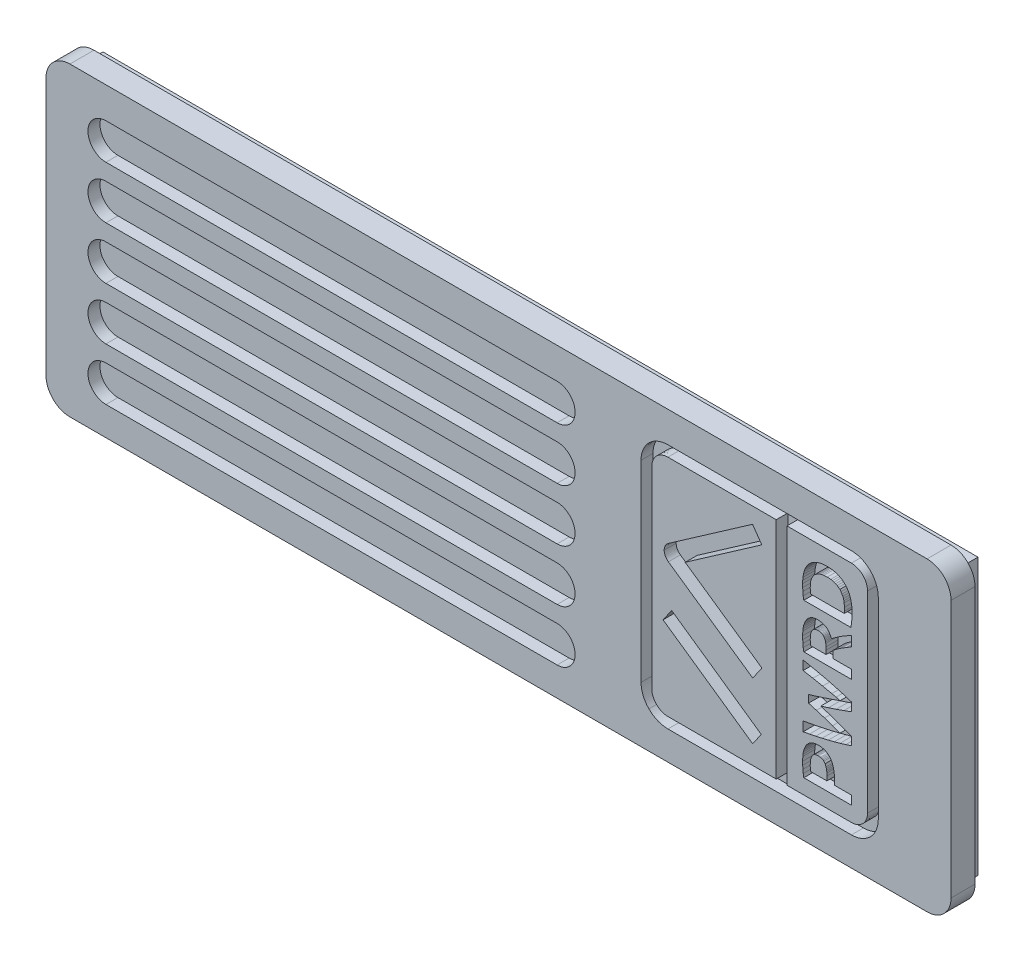
SolidWorks part; units mm, degrees
ref_plane "Front Plane" through (0, 0, 0) normal (0, 0, 1) x (1, 0, 0)
ref_plane "Top Plane" through (0, 0, 0) normal (0, 1, 0) x (1, 0, 0)
ref_plane "Right Plane" through (0, 0, 0) normal (1, 0, 0) x (0, 0, -1)
sketch "Sketch1" plane through (0, 0, 0) normal (0, 0, 1) x (1, 0, 0)
  line L1 (-35.125, 12.5203) -> (40.375, 12.5203)
  line L2 (-35.125, 12.5203) -> (-35.125, -12.9797)
  line L3 (-35.125, -12.9797) -> (40.375, -12.9797)
  line L4 (40.375, 12.5203) -> (40.375, -12.9797)
  dimension "D1" = 25.5
  dimension "D2" = 75.5
extrude "Boss-Extrude1" add sketch "Sketch1" along normal blind 2
sketch "Sketch2" plane through (0, 0, 0) normal (0, 0, -1) x (-1, 0, 0)
  line L0 (-40.375, -12.9797) -> (-40.375, 12.5203) construction
  line L1 (-39.125, 11.2703) -> (33.875, 11.2703)
  line L2 (-39.125, 11.2703) -> (-39.125, -11.7297)
  line L3 (-39.125, -11.7297) -> (33.875, -11.7297)
  line L4 (33.875, 11.2703) -> (33.875, -11.7297)
  line L5 (-40.375, 12.5203) -> (35.125, 12.5203) construction
  line L6 (35.125, -12.9797) -> (-40.375, -12.9797) construction
  line L7 (35.125, 12.5203) -> (35.125, -12.9797) construction
  line L9 (-38.625, 10.7703) -> (33.375, 10.7703)
  line L10 (-38.625, 10.7703) -> (-38.625, -11.2297)
  line L11 (-38.625, -11.2297) -> (33.375, -11.2297)
  line L12 (33.375, 10.7703) -> (33.375, -11.2297)
  dimension "D1" = 1.25
  dimension "D2" = 1.25
  dimension "D3" = 1.25
  dimension "D4" = 1.25
  dimension "D5" = 0.5
  dimension "D6" = 0.5
  dimension "D7" = 0.5
  dimension "D8" = 0.5
extrude "Boss-Extrude2" add sketch "Sketch2" along normal blind 1.5
fillet "Fillet1" radius 2 4 edges at (40.375, 12.5203, 1) (40.375, -12.9797, 1) (-35.125, -12.9797, 1) (-35.125, 12.5203, 1)
sketch "Sketch4" plane through (0, 0, 2) normal (0, 0, 1) x (1, 0, 0)
  line L4 (14.5143, -8.3343) -> (14.5143, 7.713)
  line L5 (16.7569, 9.9556) -> (32.0631, 9.9556)
  line L6 (34.3057, 7.713) -> (34.3057, -8.3343)
  line L7 (32.0631, -10.5769) -> (16.7569, -10.5769)
  line L8 (26.6901, 9.0585) -> (26.6901, -9.6798)
  line L9 (26.6901, -9.6798) -> (32.0631, -9.6798)
  line L10 (33.4087, -8.3343) -> (33.4087, 7.713)
  line L11 (32.0631, 9.0585) -> (26.6901, 9.0585)
  line L12 (28.094, -8.4335) -> (28.0437, -8.1511)
  line L13 (28.0437, -8.1511) -> (28.0159, -7.8656)
  line L14 (28.0159, -7.8656) -> (28.0016, -7.5789)
  line L15 (28.0016, -7.5789) -> (27.996, -7.2918)
  line L16 (27.996, -7.2918) -> (28.0095, -6.9377)
  line L17 (28.0095, -6.9377) -> (28.0265, -6.7634)
  line L18 (28.0265, -6.7634) -> (28.0561, -6.5922)
  line L19 (28.0561, -6.5922) -> (28.1028, -6.4253)
  line L20 (28.1028, -6.4253) -> (28.1647, -6.2624)
  line L21 (28.1647, -6.2624) -> (28.2373, -6.1022)
  line L22 (28.2373, -6.1022) -> (28.3154, -5.9434)
  line L23 (28.3154, -5.9434) -> (28.417, -5.8361)
  line L24 (28.417, -5.8361) -> (28.5218, -5.7352)
  line L25 (28.5218, -5.7352) -> (28.6328, -5.6473)
  line L26 (28.6328, -5.6473) -> (28.692, -5.6102)
  line L27 (28.692, -5.6102) -> (28.7539, -5.5788)
  line L28 (28.7539, -5.5788) -> (28.8185, -5.553)
  line L29 (28.8185, -5.553) -> (28.8858, -5.5324)
  line L30 (28.8858, -5.5324) -> (29.0254, -5.5034)
  line L31 (29.0254, -5.5034) -> (29.1706, -5.486)
  line L32 (29.1706, -5.486) -> (29.3187, -5.4745)
  line L33 (29.3187, -5.4745) -> (29.476, -5.482)
  line L34 (29.476, -5.482) -> (29.6305, -5.502)
  line L35 (29.6305, -5.502) -> (29.7804, -5.5438)
  line L36 (29.7804, -5.5438) -> (29.9274, -5.5997)
  line L37 (29.9274, -5.5997) -> (30.0475, -5.6717)
  line L38 (30.0475, -5.6717) -> (30.1584, -5.7541)
  line L39 (30.1584, -5.7541) -> (30.2542, -5.8538)
  line L40 (30.2542, -5.8538) -> (30.3413, -5.9637)
  line L41 (30.3413, -5.9637) -> (30.4193, -6.1016)
  line L42 (30.4193, -6.1016) -> (30.4866, -6.2438)
  line L43 (30.4866, -6.2438) -> (30.5368, -6.393)
  line L44 (30.5368, -6.393) -> (30.5772, -6.5462)
  line L45 (30.5772, -6.5462) -> (30.6113, -6.7414)
  line L46 (30.6113, -6.7414) -> (30.6364, -6.9373)
  line L47 (30.6364, -6.9373) -> (30.6489, -7.1346)
  line L48 (30.6489, -7.1346) -> (30.6535, -7.3326)
  line L49 (30.6535, -7.3326) -> (30.6535, -7.6996)
  line L50 (30.6535, -7.6996) -> (32.0748, -7.6996)
  line L51 (32.0748, -7.6996) -> (32.0748, -8.4335)
  line L52 (32.0748, -8.4335) -> (28.094, -8.4335)
  line L53 (28.4871, 7.186) -> (28.6281, 7.3283)
  line L54 (28.6281, 7.3283) -> (28.7016, 7.3948)
  line L55 (28.7016, 7.3948) -> (28.7797, 7.4559)
  line L56 (28.7797, 7.4559) -> (28.8622, 7.5104)
  line L57 (28.8622, 7.5104) -> (28.9483, 7.5595)
  line L58 (28.9483, 7.5595) -> (29.1275, 7.6491)
  line L59 (29.1275, 7.6491) -> (29.3524, 7.722)
  line L60 (29.3524, 7.722) -> (29.4659, 7.7527)
  line L61 (29.4659, 7.7527) -> (29.5806, 7.7765)
  line L62 (29.5806, 7.7765) -> (29.6969, 7.7925)
  line L63 (29.6969, 7.7925) -> (29.8142, 7.8025)
  line L64 (29.8142, 7.8025) -> (30.0508, 7.8121)
  line L65 (30.0508, 7.8121) -> (30.2844, 7.8022)
  line L66 (30.2844, 7.8022) -> (30.4003, 7.7921)
  line L67 (30.4003, 7.7921) -> (30.515, 7.7761)
  line L68 (30.515, 7.7761) -> (30.6283, 7.7522)
  line L69 (30.6283, 7.7522) -> (30.7403, 7.7216)
  line L70 (30.7403, 7.7216) -> (30.9623, 7.6491)
  line L71 (30.9623, 7.6491) -> (31.1426, 7.5591)
  line L72 (31.1426, 7.5591) -> (31.2296, 7.5098)
  line L73 (31.2296, 7.5098) -> (31.313, 7.4553)
  line L74 (31.313, 7.4553) -> (31.3919, 7.3943)
  line L75 (31.3919, 7.3943) -> (31.4664, 7.3279)
  line L76 (31.4664, 7.3279) -> (31.6093, 7.186)
  line L77 (31.6093, 7.186) -> (31.7323, 7.0199)
  line L78 (31.7323, 7.0199) -> (31.7888, 6.9343)
  line L79 (31.7888, 6.9343) -> (31.8399, 6.8457)
  line L80 (31.8399, 6.8457) -> (31.8848, 6.7535)
  line L81 (31.8848, 6.7535) -> (31.9242, 6.6585)
  line L82 (31.9242, 6.6585) -> (31.9942, 6.4637)
  line L83 (31.9942, 6.4637) -> (32.0489, 6.2332)
  line L84 (32.0489, 6.2332) -> (32.0902, 6.0009)
  line L85 (32.0902, 6.0009) -> (32.1108, 5.7657)
  line L86 (32.1108, 5.7657) -> (32.1192, 5.5288)
  line L87 (32.1192, 5.5288) -> (32.1132, 5.252)
  line L88 (32.1132, 5.252) -> (32.0989, 4.9755)
  line L89 (32.0989, 4.9755) -> (32.0684, 4.6796)
  line L90 (32.0684, 4.6796) -> (32.0146, 4.3871)
  line L91 (32.0146, 4.3871) -> (28.0944, 4.3871)
  line L92 (28.0944, 4.3871) -> (28.0406, 4.6825)
  line L93 (28.0406, 4.6825) -> (28.0128, 4.9813)
  line L94 (28.0128, 4.9813) -> (28.0002, 5.2608)
  line L95 (28.0002, 5.2608) -> (27.9953, 5.5405)
  line L96 (27.9953, 5.5405) -> (28.0033, 5.7749)
  line L97 (28.0033, 5.7749) -> (28.023, 6.0078)
  line L98 (28.023, 6.0078) -> (28.0625, 6.238)
  line L99 (28.0625, 6.238) -> (28.1145, 6.4666)
  line L100 (28.1145, 6.4666) -> (28.1818, 6.6602)
  line L101 (28.1818, 6.6602) -> (28.2194, 6.7547)
  line L102 (28.2194, 6.7547) -> (28.2625, 6.8465)
  line L103 (28.2625, 6.8465) -> (28.3118, 6.9347)
  line L104 (28.3118, 6.9347) -> (28.3674, 7.0201)
  line L105 (28.3674, 7.0201) -> (28.4871, 7.186)
  line L106 (28.7697, -6.5288) -> (28.7329, -6.6049)
  line L107 (28.7329, -6.6049) -> (28.7015, -6.6828)
  line L108 (28.7015, -6.6828) -> (28.6611, -6.8462)
  line L109 (28.6611, -6.8462) -> (28.6369, -7.0421)
  line L110 (28.6369, -7.0421) -> (28.6294, -7.2394)
  line L111 (28.6294, -7.2394) -> (28.6328, -7.4697)
  line L112 (28.6328, -7.4697) -> (28.6471, -7.6996)
  line L113 (28.6471, -7.6996) -> (30.0218, -7.6996)
  line L114 (30.0218, -7.6996) -> (30.0218, -7.3443)
  line L115 (30.0218, -7.3443) -> (30.0161, -7.1342)
  line L116 (30.0161, -7.1342) -> (30.0083, -7.0301)
  line L117 (30.0083, -7.0301) -> (29.9948, -6.9272)
  line L118 (29.9948, -6.9272) -> (29.9733, -6.8259)
  line L119 (29.9733, -6.8259) -> (29.9446, -6.726)
  line L120 (29.9446, -6.726) -> (29.8737, -6.5288)
  line L121 (29.8737, -6.5288) -> (29.7644, -6.3992)
  line L122 (29.7644, -6.3992) -> (29.7043, -6.3449)
  line L123 (29.7043, -6.3449) -> (29.6371, -6.3033)
  line L124 (29.6371, -6.3033) -> (29.5626, -6.2757)
  line L125 (29.5626, -6.2757) -> (29.4819, -6.2589)
  line L126 (29.4819, -6.2589) -> (29.3114, -6.2434)
  line L127 (29.3114, -6.2434) -> (29.2252, -6.2478)
  line L128 (29.2252, -6.2478) -> (29.1409, -6.2597)
  line L129 (29.1409, -6.2597) -> (29.0593, -6.2851)
  line L130 (29.0593, -6.2851) -> (28.9794, -6.3191)
  line L131 (28.9794, -6.3191) -> (28.9167, -6.3615)
  line L132 (28.9167, -6.3615) -> (28.8601, -6.4094)
  line L133 (28.8601, -6.4094) -> (28.8126, -6.4663)
  line L134 (28.8126, -6.4663) -> (28.7697, -6.5288)
  line L135 (28.6299, 5.5871) -> (28.6323, 5.3538)
  line L136 (28.6323, 5.3538) -> (28.6476, 5.1211)
  line L137 (28.6476, 5.1211) -> (31.4669, 5.1211)
  line L138 (31.4669, 5.1211) -> (31.4756, 5.29)
  line L139 (31.4756, 5.29) -> (31.4785, 5.5754)
  line L140 (31.4785, 5.5754) -> (31.4606, 5.8788)
  line L141 (31.4606, 5.8788) -> (31.439, 6.0261)
  line L142 (31.439, 6.0261) -> (31.4032, 6.1682)
  line L143 (31.4032, 6.1682) -> (31.3484, 6.3034)
  line L144 (31.3484, 6.3034) -> (31.2767, 6.4322)
  line L145 (31.2767, 6.4322) -> (31.1932, 6.5568)
  line L146 (31.1932, 6.5568) -> (31.1035, 6.6793)
  line L147 (31.1035, 6.6793) -> (30.9862, 6.764)
  line L148 (30.9862, 6.764) -> (30.8671, 6.8435)
  line L149 (30.8671, 6.8435) -> (30.7441, 6.9124)
  line L150 (30.7441, 6.9124) -> (30.6155, 6.9655)
  line L151 (30.6155, 6.9655) -> (30.4804, 7.0009)
  line L152 (30.4804, 7.0009) -> (30.3403, 7.0227)
  line L153 (30.3403, 7.0227) -> (30.052, 7.0433)
  line L154 (30.052, 7.0433) -> (29.7636, 7.0244)
  line L155 (29.7636, 7.0244) -> (29.6234, 7.0037)
  line L156 (29.6234, 7.0037) -> (29.4881, 6.9695)
  line L157 (29.4881, 6.9695) -> (29.3589, 6.9177)
  line L158 (29.3589, 6.9177) -> (29.2354, 6.85)
  line L159 (29.2354, 6.85) -> (29.1156, 6.7717)
  line L160 (29.1156, 6.7717) -> (28.9977, 6.688)
  line L161 (28.9977, 6.688) -> (28.9089, 6.5656)
  line L162 (28.9089, 6.5656) -> (28.8264, 6.4411)
  line L163 (28.8264, 6.4411) -> (28.7555, 6.3124)
  line L164 (28.7555, 6.3124) -> (28.7026, 6.1775)
  line L165 (28.7026, 6.1775) -> (28.6676, 6.0358)
  line L166 (28.6676, 6.0358) -> (28.647, 5.8891)
  line L167 (28.647, 5.8891) -> (28.6299, 5.5871)
  line L168 (30.5463, 1.8591) -> (30.5463, 1.3931)
  line L169 (30.5463, 1.3931) -> (32.0724, 1.3931)
  line L170 (32.0724, 1.3931) -> (32.0724, 0.6592)
  line L171 (32.0724, 0.6592) -> (28.094, 0.6592)
  line L172 (28.094, 0.6592) -> (28.0446, 0.9432)
  line L173 (28.0446, 0.9432) -> (28.0159, 1.23)
  line L174 (28.0159, 1.23) -> (28.0016, 1.5007)
  line L175 (28.0016, 1.5007) -> (27.9959, 1.7717)
  line L176 (27.9959, 1.7717) -> (28.0093, 2.1231)
  line L177 (28.0093, 2.1231) -> (28.0264, 2.2961)
  line L178 (28.0264, 2.2961) -> (28.056, 2.4658)
  line L179 (28.056, 2.4658) -> (28.1026, 2.6312)
  line L180 (28.1026, 2.6312) -> (28.1645, 2.7926)
  line L181 (28.1645, 2.7926) -> (28.2372, 2.9513)
  line L182 (28.2372, 2.9513) -> (28.3152, 3.1086)
  line L183 (28.3152, 3.1086) -> (28.4145, 3.2137)
  line L184 (28.4145, 3.2137) -> (28.5168, 3.3126)
  line L185 (28.5168, 3.3126) -> (28.6251, 3.3991)
  line L186 (28.6251, 3.3991) -> (28.6826, 3.4357)
  line L187 (28.6826, 3.4357) -> (28.7427, 3.4668)
  line L188 (28.7427, 3.4668) -> (28.8054, 3.4924)
  line L189 (28.8054, 3.4924) -> (28.8709, 3.5129)
  line L190 (28.8709, 3.5129) -> (29.0074, 3.542)
  line L191 (29.0074, 3.542) -> (29.1493, 3.5596)
  line L192 (29.1493, 3.5596) -> (29.294, 3.5717)
  line L193 (29.294, 3.5717) -> (29.4851, 3.5429)
  line L194 (29.4851, 3.5429) -> (29.6696, 3.5047)
  line L195 (29.6696, 3.5047) -> (29.7575, 3.4793)
  line L196 (29.7575, 3.4793) -> (29.8409, 3.448)
  line L197 (29.8409, 3.448) -> (29.9189, 3.4097)
  line L198 (29.9189, 3.4097) -> (29.9916, 3.3631)
  line L199 (29.9916, 3.3631) -> (30.058, 3.3077)
  line L200 (30.058, 3.3077) -> (30.1181, 3.2445)
  line L201 (30.1181, 3.2445) -> (30.1737, 3.1744)
  line L202 (30.1737, 3.1744) -> (30.2248, 3.0987)
  line L203 (30.2248, 3.0987) -> (30.3188, 2.9349)
  line L204 (30.3188, 2.9349) -> (30.4059, 2.762)
  line L205 (30.4059, 2.762) -> (30.5671, 2.8897)
  line L206 (30.5671, 2.8897) -> (30.732, 3.0125)
  line L207 (30.732, 3.0125) -> (30.9383, 3.1579)
  line L208 (30.9383, 3.1579) -> (31.1484, 3.2979)
  line L209 (31.1484, 3.2979) -> (31.3765, 3.4411)
  line L210 (31.3765, 3.4411) -> (31.6086, 3.5775)
  line L211 (31.6086, 3.5775) -> (31.8377, 3.7018)
  line L212 (31.8377, 3.7018) -> (32.0717, 3.8163)
  line L213 (32.0717, 3.8163) -> (32.0717, 2.995)
  line L214 (32.0717, 2.995) -> (31.8589, 2.8786)
  line L215 (31.8589, 2.8786) -> (31.6494, 2.7562)
  line L216 (31.6494, 2.7562) -> (31.2359, 2.497)
  line L217 (31.2359, 2.497) -> (31.0451, 2.3696)
  line L218 (31.0451, 2.3696) -> (30.8573, 2.2377)
  line L219 (30.8573, 2.2377) -> (30.5399, 1.9989)
  line L220 (30.5399, 1.9989) -> (30.5463, 1.8591)
  line L221 (28.7697, 2.5319) -> (28.7329, 2.4573)
  line L222 (28.7329, 2.4573) -> (28.7015, 2.3808)
  line L223 (28.7015, 2.3808) -> (28.6611, 2.2203)
  line L224 (28.6611, 2.2203) -> (28.6369, 2.0229)
  line L225 (28.6369, 2.0229) -> (28.6295, 1.8242)
  line L226 (28.6295, 1.8242) -> (28.6336, 1.6085)
  line L227 (28.6336, 1.6085) -> (28.647, 1.3931)
  line L228 (28.647, 1.3931) -> (29.9518, 1.3931)
  line L229 (29.9518, 1.3931) -> (29.9518, 1.7135)
  line L230 (29.9518, 1.7135) -> (29.9455, 1.9499)
  line L231 (29.9455, 1.9499) -> (29.9231, 2.1853)
  line L232 (29.9231, 2.1853) -> (29.9069, 2.2738)
  line L233 (29.9069, 2.2738) -> (29.8854, 2.3605)
  line L234 (29.8854, 2.3605) -> (29.8549, 2.4443)
  line L235 (29.8549, 2.4443) -> (29.8181, 2.5261)
  line L236 (29.8181, 2.5261) -> (29.7777, 2.588)
  line L237 (29.7777, 2.588) -> (29.732, 2.6444)
  line L238 (29.732, 2.6444) -> (29.6764, 2.6915)
  line L239 (29.6764, 2.6915) -> (29.6154, 2.733)
  line L240 (29.6154, 2.733) -> (29.5373, 2.7647)
  line L241 (29.5373, 2.7647) -> (29.4575, 2.7882)
  line L242 (29.4575, 2.7882) -> (29.3741, 2.7991)
  line L243 (29.3741, 2.7991) -> (29.2898, 2.8029)
  line L244 (29.2898, 2.8029) -> (29.2081, 2.7987)
  line L245 (29.2081, 2.7987) -> (29.1283, 2.7876)
  line L246 (29.1283, 2.7876) -> (29.0511, 2.7642)
  line L247 (29.0511, 2.7642) -> (28.9758, 2.7329)
  line L248 (28.9758, 2.7329) -> (28.9148, 2.6925)
  line L249 (28.9148, 2.6925) -> (28.8592, 2.6468)
  line L250 (28.8592, 2.6468) -> (28.8125, 2.5921)
  line L251 (28.8125, 2.5921) -> (28.7697, 2.5319)
  line L252 (25.7931, 9.0585) -> (16.7569, 9.0585)
  line L253 (15.4114, 7.713) -> (15.4114, -8.3343)
  line L254 (16.7569, -9.6798) -> (25.7931, -9.6798)
  line L255 (25.7931, -9.6798) -> (25.7931, 9.0585)
  line L256 (29.1424, -3.0367) -> (28.49, -2.8474)
  line L257 (28.49, -2.8474) -> (28.49, -2.2183)
  line L258 (28.49, -2.2183) -> (29.1453, -2.0203)
  line L259 (29.1453, -2.0203) -> (29.8268, -1.8018)
  line L260 (29.8268, -1.8018) -> (30.4966, -1.5747)
  line L261 (30.4966, -1.5747) -> (31.117, -1.3562)
  line L262 (31.117, -1.3562) -> (30.776, -1.2671)
  line L263 (30.776, -1.2671) -> (30.4326, -1.1873)
  line L264 (30.4326, -1.1873) -> (29.6637, -1.0242)
  line L265 (29.6637, -1.0242) -> (28.8512, -0.864)
  line L266 (28.8512, -0.864) -> (28.0357, -0.7155)
  line L267 (28.0357, -0.7155) -> (28.0357, 0.0418)
  line L268 (28.0357, 0.0418) -> (28.5644, -0.0611)
  line L269 (28.5644, -0.0611) -> (29.0919, -0.1696)
  line L270 (29.0919, -0.1696) -> (29.6172, -0.2879)
  line L271 (29.6172, -0.2879) -> (30.1414, -0.412)
  line L272 (30.1414, -0.412) -> (30.6279, -0.5382)
  line L273 (30.6279, -0.5382) -> (31.1124, -0.6717)
  line L274 (31.1124, -0.6717) -> (31.5934, -0.8173)
  line L275 (31.5934, -0.8173) -> (32.0723, -0.9703)
  line L276 (32.0723, -0.9703) -> (32.0723, -1.6766)
  line L277 (32.0723, -1.6766) -> (31.4356, -1.911)
  line L278 (31.4356, -1.911) -> (30.7958, -2.1364)
  line L279 (30.7958, -2.1364) -> (30.1511, -2.3475)
  line L280 (30.1511, -2.3475) -> (29.5036, -2.5503)
  line L281 (29.5036, -2.5503) -> (30.1756, -2.7626)
  line L282 (30.1756, -2.7626) -> (30.8433, -2.9878)
  line L283 (30.8433, -2.9878) -> (31.459, -3.2061)
  line L284 (31.459, -3.2061) -> (32.0724, -3.431)
  line L285 (32.0724, -3.431) -> (32.0724, -4.1313)
  line L286 (32.0724, -4.1313) -> (31.594, -4.2863)
  line L287 (31.594, -4.2863) -> (31.1132, -4.4331)
  line L288 (31.1132, -4.4331) -> (30.6286, -4.5665)
  line L289 (30.6286, -4.5665) -> (30.1416, -4.6921)
  line L290 (30.1416, -4.6921) -> (29.6172, -4.8148)
  line L291 (29.6172, -4.8148) -> (29.0917, -4.932)
  line L292 (29.0917, -4.932) -> (28.5643, -5.0399)
  line L293 (28.5643, -5.0399) -> (28.0357, -5.1424)
  line L294 (28.0357, -5.1424) -> (28.0357, -4.3561)
  line L295 (28.0357, -4.3561) -> (28.8454, -4.2075)
  line L296 (28.8454, -4.2075) -> (29.6579, -4.0444)
  line L297 (29.6579, -4.0444) -> (30.4297, -3.8726)
  line L298 (30.4297, -3.8726) -> (30.7743, -3.7887)
  line L299 (30.7743, -3.7887) -> (31.117, -3.6979)
  line L300 (31.117, -3.6979) -> (30.4908, -3.4736)
  line L301 (30.4908, -3.4736) -> (29.821, -3.2493)
  line L302 (29.821, -3.2493) -> (29.1424, -3.0367)
  line L303 (24.5456, -7.0798) -> (23.8253, -8.1118)
  line L304 (23.8253, -8.1118) -> (16.3511, -2.8951)
  line L305 (16.3511, -2.8951) -> (17.0713, -1.8631)
  line L306 (17.0713, -1.8631) -> (24.5456, -7.0798)
  line L307 (16.7924, 2.8449) -> (23.819, 7.7411)
  line L308 (23.819, 7.7411) -> (24.5883, 6.6371)
  line L309 (24.5883, 6.6371) -> (18.1969, 2.1835)
  line L310 (18.1969, 2.1835) -> (24.5988, -2.2563)
  line L311 (24.5988, -2.2563) -> (23.8319, -3.362)
  line L312 (23.8319, -3.362) -> (16.7939, 1.5191)
  spline S0 degree 3 poles (14.5143, 7.713) (14.5143, 8.3077) (14.7506, 8.8781) (15.1712, 9.2987) knots 0 0 0 0 1 1 1 1
  spline S1 degree 3 poles (15.1712, 9.2987) (15.5918, 9.7193) (16.1622, 9.9556) (16.7569, 9.9556) knots 0 0 0 0 1 1 1 1
  spline S2 degree 3 poles (32.0631, 9.9556) (33.3017, 9.9556) (34.3057, 8.9515) (34.3057, 7.713) knots 0 0 0 0 1 1 1 1
  spline S3 degree 3 poles (34.3057, -8.3343) (34.3057, -9.5728) (33.3017, -10.5769) (32.0631, -10.5769) knots 0 0 0 0 1 1 1 1
  spline S4 degree 3 poles (16.7569, -10.5769) (16.1622, -10.5769) (15.5918, -10.3406) (15.1712, -9.92) knots 0 0 0 0 1 1 1 1
  spline S5 degree 3 poles (15.1712, -9.92) (14.7506, -9.4995) (14.5143, -8.929) (14.5143, -8.3343) knots 0 0 0 0 1 1 1 1
  spline S6 degree 3 poles (32.0631, -9.6798) (32.8063, -9.6798) (33.4087, -9.0774) (33.4087, -8.3343) knots 0 0 0 0 1 1 1 1
  spline S7 degree 3 poles (33.4087, 7.713) (33.4087, 8.4561) (32.8063, 9.0585) (32.0631, 9.0585) knots 0 0 0 0 1 1 1 1
  spline S8 degree 3 poles (16.7569, 9.0585) (16.4001, 9.0585) (16.0578, 8.9168) (15.8055, 8.6644) knots 0 0 0 0 1 1 1 1
  spline S9 degree 3 poles (15.8055, 8.6644) (15.5531, 8.4121) (15.4114, 8.0698) (15.4114, 7.713) knots 0 0 0 0 1 1 1 1
  spline S10 degree 3 poles (15.4114, -8.3343) (15.4114, -8.6911) (15.5531, -9.0334) (15.8055, -9.2857) knots 0 0 0 0 1 1 1 1
  spline S11 degree 3 poles (15.8055, -9.2857) (16.0578, -9.5381) (16.4001, -9.6798) (16.7569, -9.6798) knots 0 0 0 0 1 1 1 1
  spline S12 degree 3 poles (16.7939, 1.5191) (16.5766, 1.6698) (16.4469, 1.9172) (16.4466, 2.1816) knots 0 0 0 0 1 1 1 1
  spline S13 degree 3 poles (16.4466, 2.1816) (16.4463, 2.446) (16.5755, 2.6938) (16.7924, 2.8449) knots 0 0 0 0 1 1 1 1
extrude "Cut-Extrude1" cut sketch "Sketch4" against normal blind 1 contours S5 S4 L7 S3 L6 S2 L5 S1 S0 L4 S11 S10 L253 S9 S8 L252 L255 L254 S7 L10 S6 L9 L8 L11 | L306 L305 L304 L303 | S13 S12 L312 L311 L310 L309 L308 L307 | L52 L51 L50 L49 L48 L47 L46 L45 L44 L43 L42 L41 L40 L39 L38 L37 L36 L35 L34 L33 L32 L31 L30 L29 L28 L27 L26 L25 L24 L23 L22 L21 L20 L19 L18 L17 L16 L15 L14 L13 L12 L134 L133 L132 L131 L130 L129 L128 L127 L126 | L302 L301 L300 L299 L298 L297 L296 L295 L294 L293 L292 L291 L290 L289 L288 L287 L286 L285 L284 L283 L282 L281 L280 L279 L278 L277 L276 L275 L274 L273 L272 L271 L270 L269 L268 L267 L266 L265 L264 L263 L262 L261 L260 L259 L258 L257 L256 | L220 L219 L218 L217 L216 L215 L214 L213 L212 L211 L210 L209 L208 L207 L206 L205 L204 L203 L202 L201 L200 L199 L198 L197 L196 L195 L194 L193 L192 L191 L190 L189 L188 L187 L186 L185 L184 L183 L182 L181 L180 L179 L178 L177 L176 L175 L174 L173 L172 L171 L170 | L105 L104 L103 L102 L101 L100 L99 L98 L97 L96 L95 L94 L93 L92 L91 L90 L89 L88 L87 L86 L85 L84 L83 L82 L81 L80 L79 L78 L77 L76 L75 L74 L73 L72 L71 L70 L69 L68 L67 L66 L65 L64 L63 L62 L61 L60 L59 L58 L57 L56 L55
sketch "Sketch6" plane through (0, 0, 2) normal (0, 0, 1) x (1, 0, 0)
  line L0 (-30.125, -9.0769) -> (7.5143, -9.0769) construction
  line L1 (-30.125, -7.5769) -> (7.5143, -7.5769)
  line L2 (-30.125, -10.5769) -> (7.5143, -10.5769)
  line L3 (-35.125, 10.5203) -> (-35.125, -10.9797) construction
  line L4 (14.5143, -8.3343) -> (14.5143, 7.713) construction
  line L6 (32.0631, -10.5769) -> (16.7569, -10.5769) construction
  line L8 (-30.125, -6.2019) -> (7.5143, -6.2019)
  line L9 (-30.125, -3.2019) -> (7.5143, -3.2019)
  line L10 (-30.125, -4.7019) -> (7.5143, -4.7019) construction
  line L11 (-30.125, -1.8269) -> (7.5143, -1.8269)
  line L12 (-30.125, 1.1731) -> (7.5143, 1.1731)
  line L13 (-30.125, -0.3269) -> (7.5143, -0.3269) construction
  line L14 (-30.125, 2.5481) -> (7.5143, 2.5481)
  line L15 (-30.125, 5.5481) -> (7.5143, 5.5481)
  line L16 (-30.125, 4.0481) -> (7.5143, 4.0481) construction
  line L17 (-30.125, 6.9231) -> (7.5143, 6.9231)
  line L18 (-30.125, 9.9231) -> (7.5143, 9.9231)
  line L19 (-30.125, 8.4231) -> (7.5143, 8.4231) construction
  arc A0 (-30.125, -7.5769) -> (-30.125, -10.5769) centre (-30.125, -9.0769) ccw
  arc A1 (7.5143, -10.5769) -> (7.5143, -7.5769) centre (7.5143, -9.0769) ccw
  arc A2 (-30.125, -3.2019) -> (-30.125, -6.2019) centre (-30.125, -4.7019) ccw
  arc A3 (7.5143, -6.2019) -> (7.5143, -3.2019) centre (7.5143, -4.7019) ccw
  arc A4 (-30.125, 1.1731) -> (-30.125, -1.8269) centre (-30.125, -0.3269) ccw
  arc A5 (7.5143, -1.8269) -> (7.5143, 1.1731) centre (7.5143, -0.3269) ccw
  arc A6 (-30.125, 5.5481) -> (-30.125, 2.5481) centre (-30.125, 4.0481) ccw
  arc A7 (7.5143, 2.5481) -> (7.5143, 5.5481) centre (7.5143, 4.0481) ccw
  arc A8 (-30.125, 9.9231) -> (-30.125, 6.9231) centre (-30.125, 8.4231) ccw
  arc A9 (7.5143, 6.9231) -> (7.5143, 9.9231) centre (7.5143, 8.4231) ccw
  point P2 (-11.3053, -9.0769)
  point P17 (-11.3053, -4.7019)
  point P24 (-11.3053, -0.3269)
  point P31 (-11.3053, 4.0481)
  point P38 (-11.3053, 8.4231)
  dimension "D1" = 3
  dimension "D2" = 5
  dimension "D3" = 7
  dimension "D4" = 0
  dimension "D5" = 5
extrude "Cut-Extrude5" cut sketch "Sketch6" against normal blind 1
